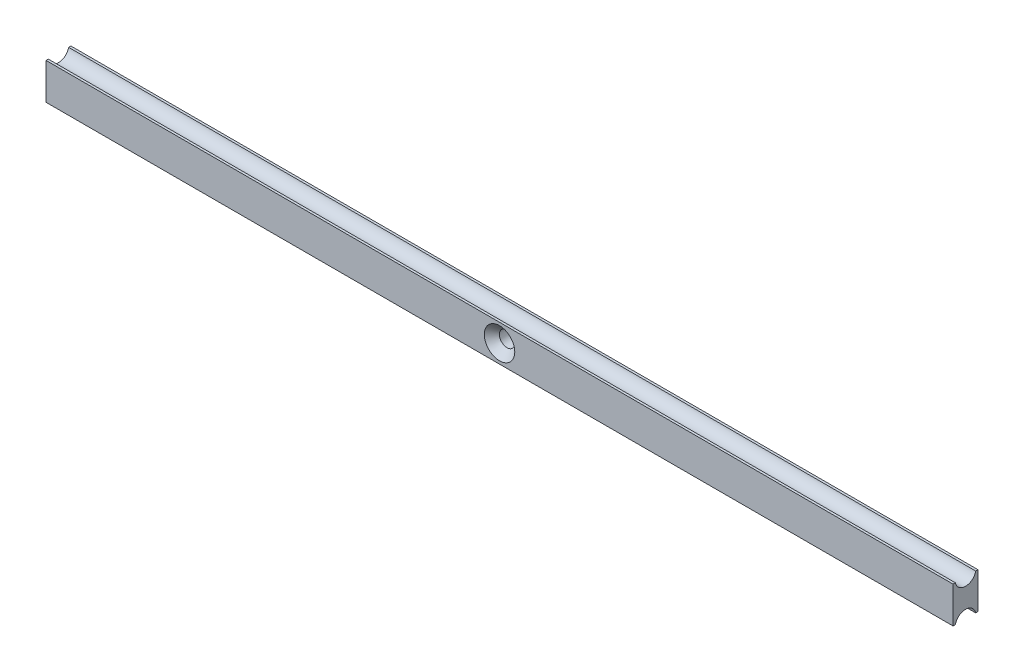
SolidWorks part; units mm, degrees
ref_plane "Front" through (0, 0, 0) normal (0, 0, 1) x (1, 0, 0)
ref_plane "Top" through (0, 0, 0) normal (0, 1, 0) x (1, 0, 0)
ref_plane "Right" through (0, 0, 0) normal (1, 0, 0) x (0, 0, -1)
sketch "Sketch1" plane through (0, 0, 0) normal (0, 0, 1) x (1, 0, 0)
  line L1 (-100, -4) -> (100, -4)
  line L2 (-100, -4) -> (-100, 4)
  line L3 (-100, 4) -> (100, 4)
  line L4 (100, -4) -> (100, 4)
  line L5 (-100, -4) -> (100, 4) construction
  line L6 (-100, 4) -> (100, -4) construction
  point P0 (0, 0)
  dimension "D1" = 200
  dimension "D2" = 8
extrude "Boss-Extrude1" add sketch "Sketch1" along normal mid plane 5.5
sketch "Sketch2" plane through (0, 0, 0) normal (1, 0, 0) x (0, 0, -1)
  line L2 (-2.75, -4) -> (2.75, -4) construction
  line L3 (-2.75, 4) -> (2.75, 4) construction
  circle A0 centre (0, 4.5) radius 2.3
  circle A1 centre (0, -4.5) radius 2.3
  dimension "D1" = 4.6
  dimension "D2" = 0.5
  dimension "D3" = 0.5
extrude "Bearing Cuts" cut sketch "Sketch2" against normal through all both and the other way through all
sketch "Sketch4" plane through (0, 0, 2.75) normal (0, 0, 1) x (1, 0, 0)
  point P0 (0, 0)
hole_wizard "CSK for M3 SFHCS1" positions "Sketch4" profile "Sketch5" countersink size "M3" standard "ANSI Metric" end condition through all
sketch "Sketch5" plane through (0, 0, 2.75) normal (1, 0, 0) x (0, -1, 0)
  line L0 (0, 0) -> (0, 5.5)
  line L1 (0, 5.5) -> (2, 5.5)
  line L2 (1.7, 5.2) -> (1.7, 1.66)
  line L3 (1.7, 1.66) -> (3.36, 0)
  line L5 (3.36, 0) -> (0, 0)
  line L6 (-1.7, 1.66) -> (-3.36, 0) construction
  line L7 (2, 5.5) -> (1.7, 5.2)
  line L8 (-2, 5.5) -> (-1.7, 5.2) construction
  line L11 (0, -6.35) -> (0, 107.95) construction
  dimension "Thru Hole Dia." = 3.4
  dimension "Thru Hole Depth" = 5.5
  dimension "Near C'Sink Dia." = 6.72
  dimension "Near C'Sink Angle" = 90
  dimension "Far C'Sink Dia." = 4
  dimension "Far C'Sink Angle" = 90
